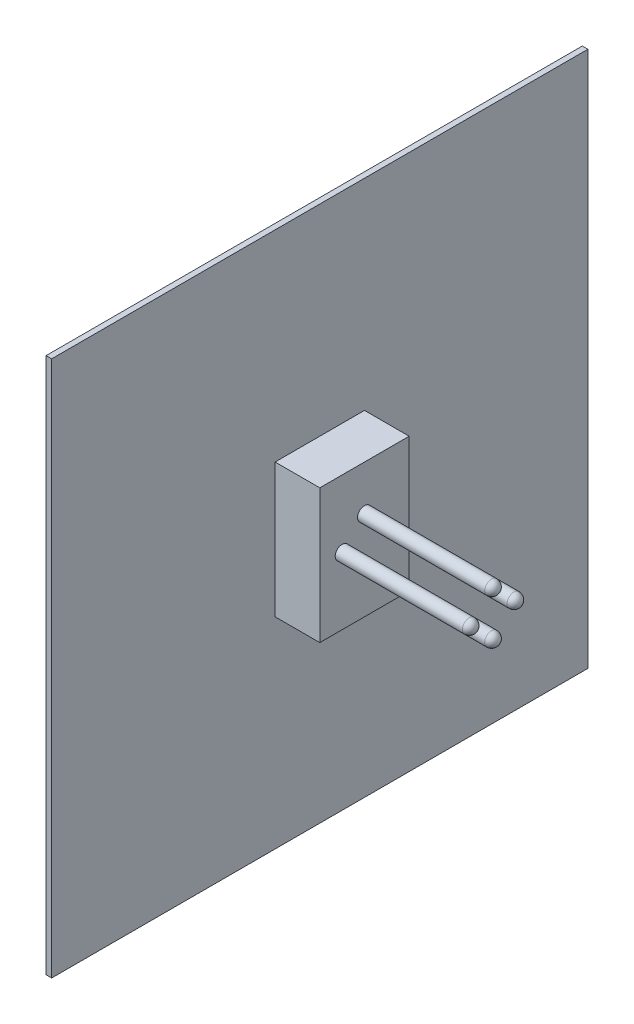
SolidWorks part; units mm, degrees
ref_plane "Front Plane" through (0, 0, 0) normal (0, 0, 1) x (1, 0, 0)
ref_plane "Top Plane" through (0, 0, 0) normal (0, 1, 0) x (1, 0, 0)
ref_plane "Right Plane" through (0, 0, 0) normal (1, 0, 0) x (0, 0, -1)
sketch "Sketch1" plane through (0, 0, 0) normal (1, 0, 0) x (0, 0, -1)
  line L1 (0, 0) -> (304.8, 0)
  line L2 (0, 0) -> (0, 304.8)
  line L3 (0, 304.8) -> (304.8, 304.8)
  line L4 (304.8, 0) -> (304.8, 304.8)
extrude "Boss-Extrude1" add sketch "Sketch1" along normal blind 3.175
sketch "Sketch2" plane through (3.175, 0, 0) normal (1, 0, 0) x (0, 0, -1)
  line L0 (0, 0) -> (304.8, 304.8) construction
  line L2 (127, 190.5) -> (177.8, 190.5)
  line L3 (127, 190.5) -> (127, 114.3)
  line L4 (127, 114.3) -> (177.8, 114.3)
  line L5 (177.8, 190.5) -> (177.8, 114.3)
  line L6 (127, 190.5) -> (177.8, 114.3) construction
  line L7 (127, 114.3) -> (177.8, 190.5) construction
  point P2 (152.4, 152.4)
extrude "Boss-Extrude2" add sketch "Sketch2" along normal blind 25.4
sketch "Sketch3" plane through (28.575, 0, 0) normal (1, 0, 0) x (0, 0, -1)
  line L0 (152.4, 190.5) -> (152.4, 114.3) construction
  line L1 (177.8, 190.5) -> (127, 190.5) construction
  line L2 (127, 114.3) -> (177.8, 114.3) construction
  line L3 (127, 152.4) -> (177.8, 152.4) construction
  line L4 (127, 190.5) -> (127, 114.3) construction
  line L5 (177.8, 114.3) -> (177.8, 190.5) construction
  circle A0 centre (152.4, 152.4) radius 4.1275
  circle A2 centre (165.1, 152.4) radius 3.937
  circle A3 centre (152.4, 165.1) radius 3.937
  circle A4 centre (139.7, 152.4) radius 3.937
  circle A5 centre (152.4, 139.7) radius 3.937
  dimension "D1" = 12.7
  dimension "D2" = 12.7
  dimension "D3" = 12.7
  dimension "D4" = 12.7
extrude "Boss-Extrude3" add sketch "Sketch3" along normal blind 76.2 contours A5 | A2 | A3 | A4
fillet "Fillet2" radius 3.937 4 edges at (104.775, 139.7, -156.337) (104.775, 152.4, -143.637) (104.775, 165.1, -156.337) (104.775, 152.4, -169.037)
